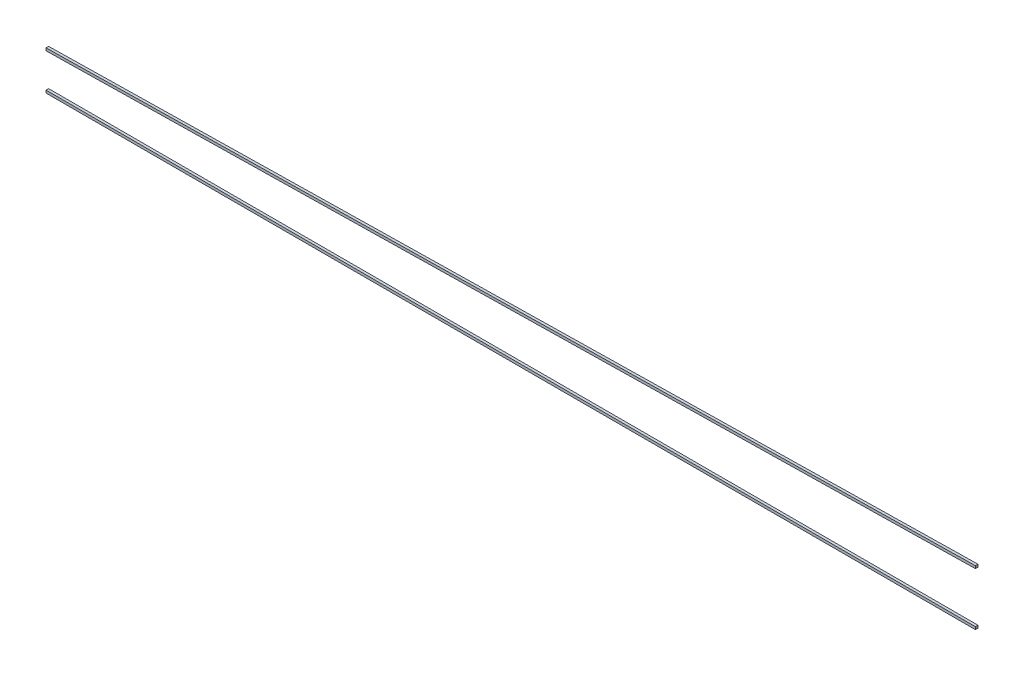
SolidWorks part; units mm, degrees
ref_plane "前视基准面" through (0, 0, 0) normal (0, 0, 1) x (1, 0, 0)
ref_plane "上视基准面" through (0, 0, 0) normal (0, 1, 0) x (1, 0, 0)
ref_plane "右视基准面" through (0, 0, 0) normal (1, 0, 0) x (0, 0, -1)
sketch "Model" plane through (0, 0, 0) normal (0, 0, 1) x (1, 0, 0)
  line L0 (271.8594, 75.1616) -> (990.591, 75.1616)
  line L1 (271.8594, 75.1616) -> (271.8594, 77.1616)
  line L2 (271.8594, 77.1616) -> (990.591, 77.1616)
  line L3 (271.8594, 103.4639) -> (990.591, 116.0094)
  line L4 (271.8594, 103.4639) -> (271.8594, 105.4639)
  line L5 (271.8594, 105.4639) -> (990.591, 118.0094)
  line L6 (990.591, 118.0094) -> (990.591, 116.0094)
  line L7 (990.591, 77.1616) -> (990.591, 75.1616)
extrude "凸台-拉伸1" add sketch "Model" along normal blind 2
